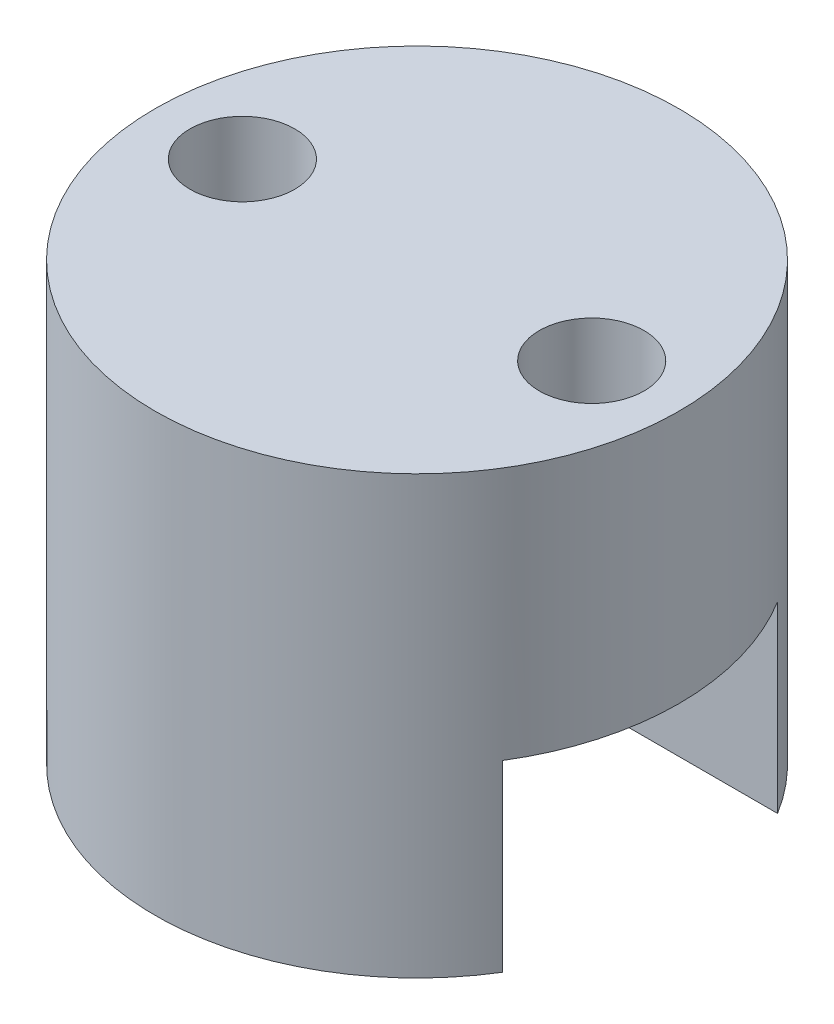
SolidWorks part; units mm, degrees
material "PETG"
ref_plane "Спереди" through (0, 0, 0) normal (0, 0, 1) x (1, 0, 0)
ref_plane "Сверху" through (0, 0, 0) normal (0, 1, 0) x (1, 0, 0)
ref_plane "Справа" through (0, 0, 0) normal (1, 0, 0) x (0, 0, -1)
sketch "Эскиз1" plane through (0, 0, 0) normal (0, 1, 0) x (1, 0, 0)
  circle A0 centre (0, 0) radius 6
  dimension "D1" = 12
extrude "Бобышка-Вытянуть1" add sketch "Эскиз1" along normal blind 10
sketch "Эскиз2" plane through (0, 0, 0) normal (0, -1, 0) x (1, 0, 0)
  line L0 (0, 0) -> (-50000, 0) construction
  line L1 (-5.1066, 3.15) -> (5.1066, 3.15)
  line L2 (-5.1066, -3.15) -> (5.1066, -3.15)
  circle A0 centre (0, 0) radius 6 construction
  arc A1 (-5.1066, 3.15) -> (-5.1066, -3.15) centre (0, 0) ccw
  arc A2 (5.1066, -3.15) -> (5.1066, 3.15) centre (0, 0) ccw
  dimension "D1" = 6.3
extrude "Вырез-Вытянуть1" cut sketch "Эскиз2" against normal blind 4.2
sketch "Эскиз3" plane through (0, 4.2, 0) normal (0, -1, 0) x (1, 0, 0)
  circle A0 centre (0, 0) radius 1.75
  dimension "D1" = 3.5
extrude "Вырез-Вытянуть2" cut sketch "Эскиз3" against normal blind 5.5
sketch "Эскиз4" plane through (0, 4.2, 0) normal (0, -1, 0) x (1, 0, 0)
  line L0 (0, 0) -> (-50000, 0) construction
  line L1 (0, 0) -> (0, 50000) construction
  circle A0 centre (-4, 0) radius 1.2
  circle A1 centre (4, 0) radius 1.2
  dimension "D1" = 2.4
  dimension "D2" = 8
extrude "Вырез-Вытянуть3" cut sketch "Эскиз4" against normal up to surface (5.8 mm away) up to face at (0, 10, 6)
